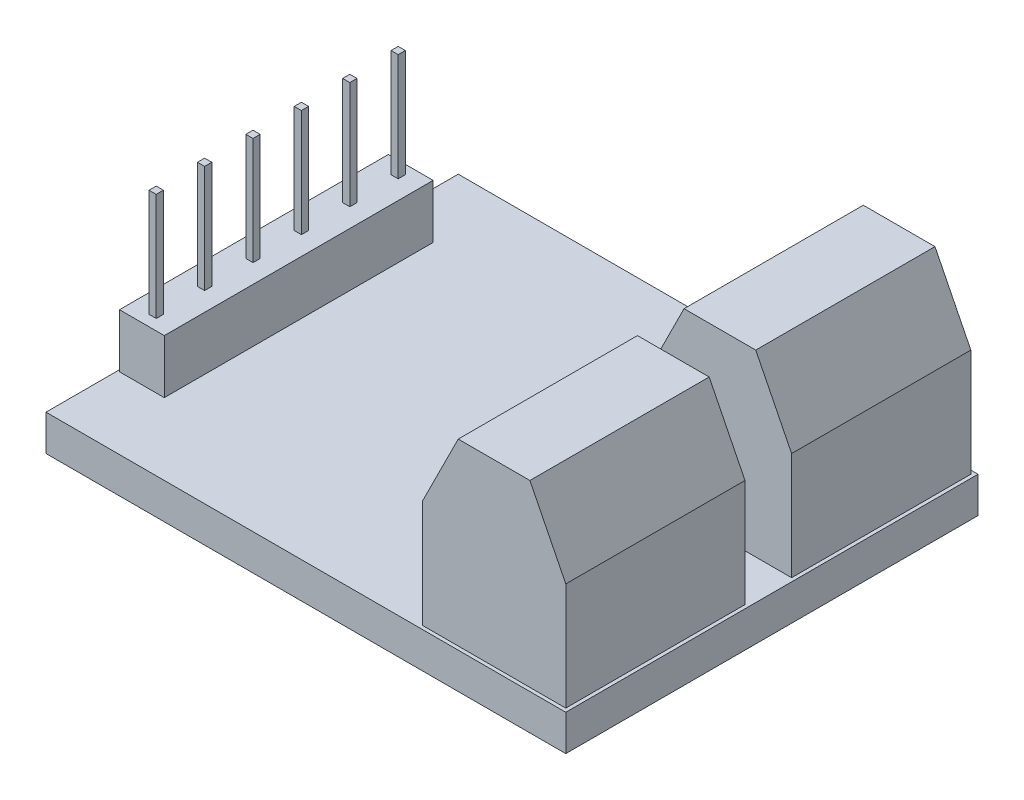
SolidWorks part; units mm, degrees
ref_plane "Front Plane" through (0, 0, 0) normal (0, 0, 1) x (1, 0, 0)
ref_plane "Top Plane" through (0, 0, 0) normal (0, 1, 0) x (1, 0, 0)
ref_plane "Right Plane" through (0, 0, 0) normal (1, 0, 0) x (0, 0, -1)
sketch "Sketch1" plane through (0, 0, 0) normal (0, 1, 0) x (1, 0, 0)
  line L1 (-14.5, -11.5) -> (14.5, -11.5)
  line L2 (-14.5, -11.5) -> (-14.5, 11.5)
  line L3 (-14.5, 11.5) -> (14.5, 11.5)
  line L4 (14.5, -11.5) -> (14.5, 11.5)
  point P4 (0, 11.5)
  point P7 (14.5, 0)
  dimension "D1" = 29
  dimension "D2" = 23
extrude "Boss-Extrude1" add sketch "Sketch1" along normal blind 2
sketch "Sketch2" plane through (0, 2, 0) normal (0, 1, 0) x (1, 0, 0)
  line L0 (-14.5, -11.5) -> (14.5, -11.5) construction
  line L1 (14.3, -11.3) -> (6.3, -11.3)
  line L2 (14.3, -11.3) -> (14.3, -1.3)
  line L3 (14.3, -1.3) -> (6.3, -1.3)
  line L4 (6.3, -11.3) -> (6.3, -1.3)
  line L5 (14.5, -11.5) -> (14.5, 11.5) construction
  line L6 (0, 0) -> (14.5, 0) construction
  line L7 (14.3, 1.3) -> (6.3, 1.3)
  line L8 (6.3, 11.3) -> (6.3, 1.3)
  line L9 (14.3, 11.3) -> (6.3, 11.3)
  line L10 (14.3, 11.3) -> (14.3, 1.3)
  dimension "D1" = 0.2
  dimension "D2" = 0.2
  dimension "D3" = 10
  dimension "D4" = 8
extrude "Boss-Extrude2" add sketch "Sketch2" along normal blind 10
sketch "Sketch3" plane through (0, 0, 11.3) normal (0, 0, 1) x (1, 0, 0)
  line L1 (6.3, 12) -> (14.3, 12) construction
  line L4 (12.3, 12) -> (14.3, 12)
  line L5 (14.3, 12) -> (14.3, 8)
  line L6 (14.3, 12) -> (14.3, 2) construction
  line L7 (14.3, 8) -> (12.3, 12)
  line L8 (10.3, 12) -> (10.3, 2) construction
  line L9 (6.3, 2) -> (14.3, 2) construction
  line L10 (6.3, 12) -> (6.3, 8)
  line L11 (8.3, 12) -> (6.3, 12)
  line L12 (6.3, 8) -> (8.3, 12)
  dimension "D1" = 4
  dimension "D3" = 2
extrude "Cut-Extrude1" cut sketch "Sketch3" against normal through all
sketch "Sketch5" plane through (0, 2, 0) normal (0, 1, 0) x (1, 0, 0)
  line L0 (-14.5, 11.5) -> (-14.5, -11.5) construction
  line L1 (-14.4, 7.5) -> (-11.9, 7.5)
  line L2 (-14.4, 7.5) -> (-14.4, -7.5)
  line L3 (-14.4, -7.5) -> (-11.9, -7.5)
  line L4 (-11.9, 7.5) -> (-11.9, -7.5)
  point P4 (-11.9, 0)
  dimension "D1" = 0.1
  dimension "D2" = 15
  dimension "D3" = 2.5
extrude "Boss-Extrude3" add sketch "Sketch5" along normal blind 3
sketch "Sketch6" plane through (0, 5, 0) normal (0, 1, 0) x (1, 0, 0)
  line L0 (-11.9, 7.5) -> (-14.4, 7.5) construction
  line L1 (-12.95, 7) -> (-13.35, 7)
  line L2 (-12.95, 7) -> (-12.95, 6.6)
  line L3 (-12.95, 6.6) -> (-13.35, 6.6)
  line L4 (-13.35, 7) -> (-13.35, 6.6)
  line L5 (-12.95, 4.3) -> (-12.95, 3.9)
  line L6 (-12.95, 4.3) -> (-13.35, 4.3)
  line L7 (-13.35, 4.3) -> (-13.35, 3.9)
  line L8 (-12.95, 3.9) -> (-13.35, 3.9)
  line L9 (-12.95, 1.6) -> (-12.95, 1.2)
  line L10 (-12.95, 1.6) -> (-13.35, 1.6)
  line L11 (-13.35, 1.6) -> (-13.35, 1.2)
  line L12 (-12.95, 1.2) -> (-13.35, 1.2)
  line L13 (-12.95, -1.1) -> (-12.95, -1.5)
  line L14 (-12.95, -1.1) -> (-13.35, -1.1)
  line L15 (-13.35, -1.1) -> (-13.35, -1.5)
  line L16 (-12.95, -1.5) -> (-13.35, -1.5)
  line L17 (-12.95, -3.8) -> (-12.95, -4.2)
  line L18 (-12.95, -3.8) -> (-13.35, -3.8)
  line L19 (-13.35, -3.8) -> (-13.35, -4.2)
  line L20 (-12.95, -4.2) -> (-13.35, -4.2)
  line L21 (-12.95, -6.5) -> (-12.95, -6.9)
  line L22 (-12.95, -6.5) -> (-13.35, -6.5)
  line L23 (-13.35, -6.5) -> (-13.35, -6.9)
  line L24 (-12.95, -6.9) -> (-13.35, -6.9)
  line L25 (-12.95, 7) -> (-12.95, 4.3) construction
  point P4 (-13.15, 7)
  point P7 (-13.15, 7.5)
  dimension "D1" = 0.5
  dimension "D2" = 0.4
  dimension "D4" = 2.7
  dimension "D3" = 6
extrude "Boss-Extrude4" add sketch "Sketch6" along normal blind 6
